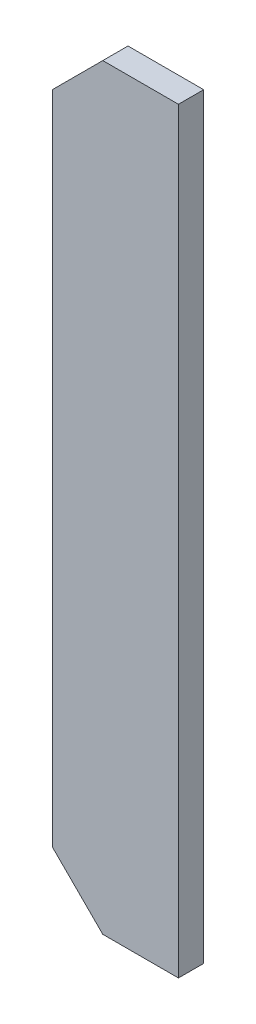
SolidWorks part; units mm, degrees
material "AISI 304"
ref_plane "Спереди" through (0, 0, 0) normal (0, 0, 1) x (1, 0, 0)
ref_plane "Сверху" through (0, 0, 0) normal (0, 1, 0) x (1, 0, 0)
ref_plane "Справа" through (0, 0, 0) normal (1, 0, 0) x (0, 0, -1)
sketch "Эскиз1" plane through (0, 0, 0) normal (0, 0, 1) x (1, 0, 0)
  line L0 (0, 0) -> (0, 150)
  line L2 (25, 0) -> (0, 0)
  line L3 (0, 150) -> (25, 150)
  line L4 (25, 150) -> (25, 0)
  dimension "D1" = 150
  dimension "D2" = 25
  dimension "D3" = 25
extrude "Бобышка-Вытянуть1" add sketch "Эскиз1" along normal mid plane 5
chamfer "Фаска1" distance 10 angle 45 2 edges at (0, 0, 0) (0, 150, 0)
